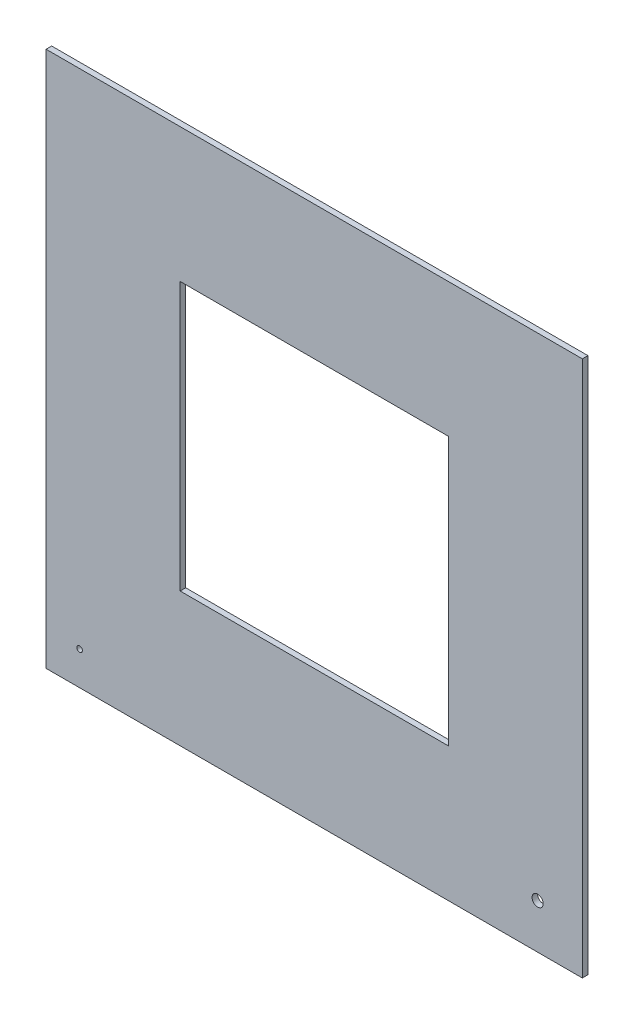
SolidWorks part; units mm, degrees
ref_plane "Front Plane" through (0, 0, 0) normal (0, 0, 1) x (1, 0, 0)
ref_plane "Top Plane" through (0, 0, 0) normal (0, 1, 0) x (1, 0, 0)
ref_plane "Right Plane" through (0, 0, 0) normal (1, 0, 0) x (0, 0, -1)
sketch "Sketch1" plane through (0, 0, 0) normal (0, 0, 1) x (1, 0, 0)
  line L1 (-304.8, 304.8) -> (304.8, 304.8)
  line L2 (-304.8, 304.8) -> (-304.8, -304.8)
  line L3 (-304.8, -304.8) -> (304.8, -304.8)
  line L4 (304.8, 304.8) -> (304.8, -304.8)
  line L5 (-304.8, 304.8) -> (304.8, -304.8) construction
  line L6 (-304.8, -304.8) -> (304.8, 304.8) construction
  point P0 (0, 0)
  dimension "D1" = 609.6
  dimension "D2" = 609.6
extrude "Boss-Extrude1" add sketch "Sketch1" along normal blind 6.35
sketch "Sketch2" plane through (0, 0, 6.35) normal (0, 0, 1) x (1, 0, 0)
  line L0 (304.8, -304.8) -> (304.8, 304.8) construction
  line L1 (-304.8, -304.8) -> (304.8, -304.8) construction
  circle A0 centre (254, -254) radius 6.35
  dimension "D1" = 50.8
  dimension "D3" = 12.7
  dimension "D2" = 50.8
extrude "Cut-Extrude1" cut sketch "Sketch2" against normal blind 6.35
sketch "Sketch3" plane through (0, 0, 6.35) normal (0, 0, 1) x (1, 0, 0)
  line L1 (-152.4, 152.4) -> (152.4, 152.4)
  line L2 (-152.4, 152.4) -> (-152.4, -152.4)
  line L3 (-152.4, -152.4) -> (152.4, -152.4)
  line L4 (152.4, 152.4) -> (152.4, -152.4)
  line L5 (-152.4, 152.4) -> (152.4, -152.4) construction
  line L6 (-152.4, -152.4) -> (152.4, 152.4) construction
  point P0 (0, 0)
  dimension "D1" = 304.8
  dimension "D2" = 304.8
extrude "Cut-Extrude2" cut sketch "Sketch3" against normal through all contours L2 L1 L4 L3
sketch "Sketch4" plane through (0, 0, 6.35) normal (0, 0, 1) x (1, 0, 0)
  line L0 (-304.8, -304.8) -> (304.8, -304.8) construction
  line L1 (-304.8, 304.8) -> (-304.8, -304.8) construction
  circle A0 centre (-266.7, -266.7) radius 3.175
  dimension "D1" = 6.35
  dimension "D2" = 38.1
  dimension "D3" = 38.1
extrude "Cut-Extrude3" cut sketch "Sketch4" against normal through all
